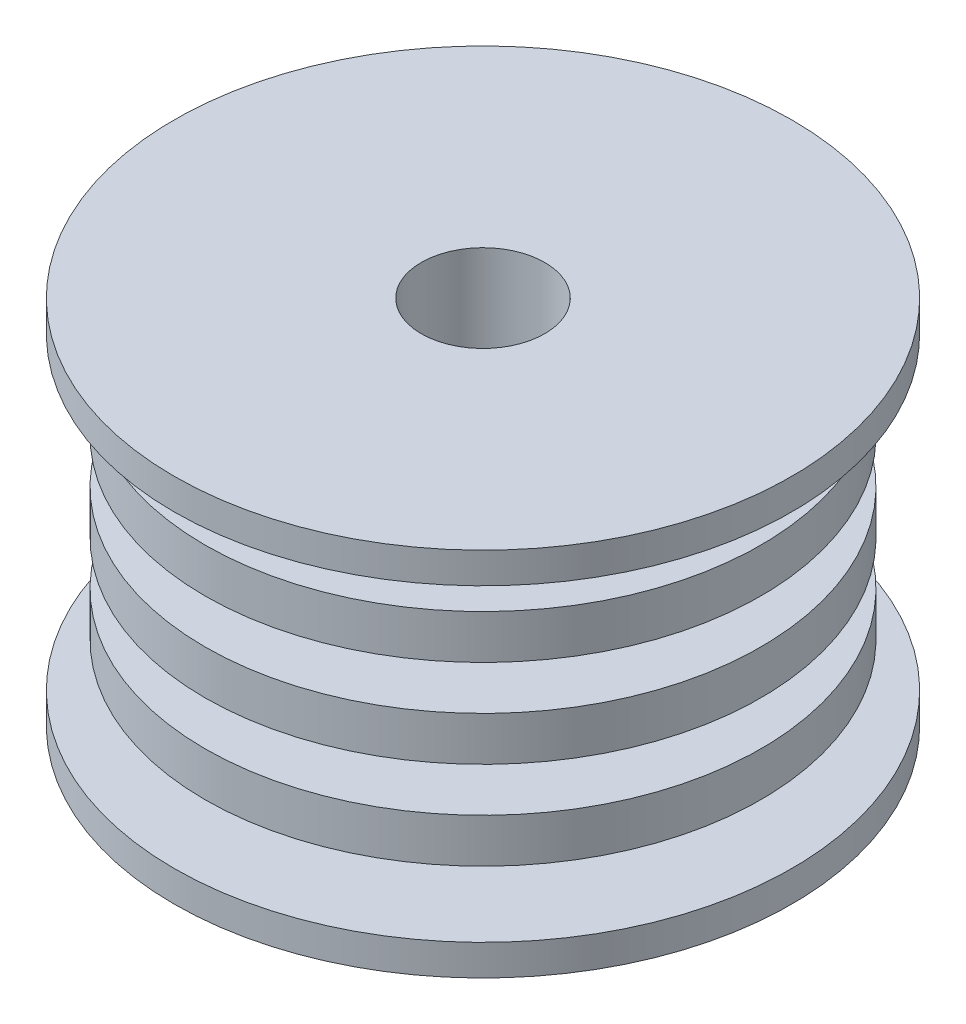
SolidWorks part; units mm, degrees
ref_plane "Front Plane" through (0, 0, 0) normal (0, 0, 1) x (1, 0, 0)
ref_plane "Top Plane" through (0, 0, 0) normal (0, 1, 0) x (1, 0, 0)
ref_plane "Right Plane" through (0, 0, 0) normal (1, 0, 0) x (0, 0, -1)
sketch "Sketch2" plane through (0, 0, 0) normal (1, 0, 0) x (0, 0, -1)
  line L0 (0, -52.0779) -> (0, 52.0779) construction
  line L1 (0, -12) -> (0, 12)
  line L2 (0, 12) -> (20, 12)
  line L3 (20, 12) -> (20, 10)
  line L4 (20, 10) -> (12, 10)
  line L5 (12, 10) -> (12, 7.1429)
  line L6 (12, 7.1429) -> (18, 7.1429)
  line L7 (18, 7.1429) -> (18, 4.2857)
  line L8 (18, 4.2857) -> (12, 4.2857)
  line L9 (12, 4.2857) -> (12, 1.4286)
  line L10 (12, 1.4286) -> (18, 1.4286)
  line L11 (18, 1.4286) -> (18, -1.4286)
  line L12 (18, -1.4286) -> (12, -1.4286)
  line L13 (12, -1.4286) -> (12, -4.2857)
  line L14 (12, -4.2857) -> (18, -4.2857)
  line L15 (18, -4.2857) -> (18, -7.1429)
  line L16 (18, -7.1429) -> (12, -7.1429)
  line L17 (12, -7.1429) -> (12, -10)
  line L18 (12, -10) -> (20, -10)
  line L19 (20, -10) -> (20, -12)
  line L20 (20, -12) -> (0, -12)
  point P4 (0, 0)
  point P8 (0, 0)
  point P25 (0, 0)
  dimension "D1" = 20
  dimension "D2" = 2
  dimension "D3" = 8
  dimension "D4" = 6
  dimension "D5" = 20
revolve "Revolve1" add sketch "Sketch2" angle 360 about L0
sketch "Sketch3" plane through (0, 12, 0) normal (0, 1, 0) x (1, 0, 0)
  circle A0 centre (0, 0) radius 4
  dimension "D1" = 8
extrude "Cut-Extrude1" cut sketch "Sketch3" against normal through all
